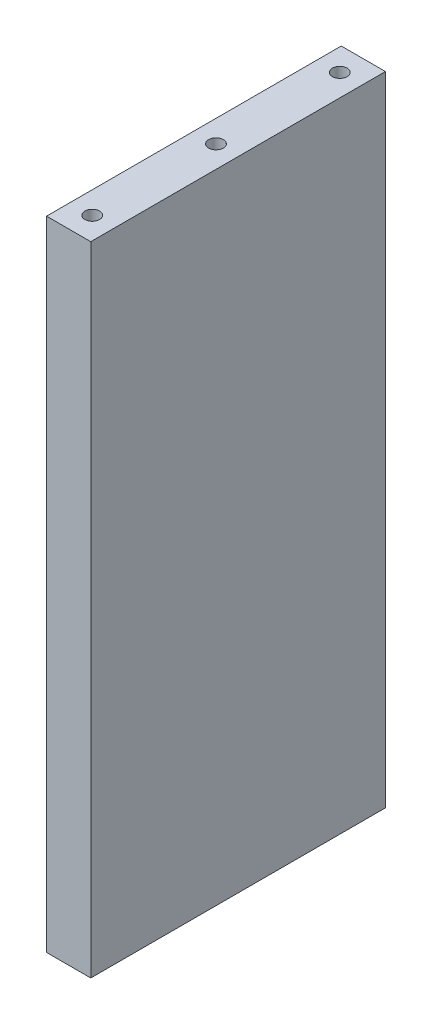
SolidWorks part; units mm, degrees
ref_plane "Front Plane" through (0, 0, 0) normal (0, 0, 1) x (1, 0, 0)
ref_plane "Top Plane" through (0, 0, 0) normal (0, 1, 0) x (1, 0, 0)
ref_plane "Right Plane" through (0, 0, 0) normal (1, 0, 0) x (0, 0, -1)
sketch "Sketch1" plane through (0, 0, 0) normal (0, 0, 1) x (1, 0, 0)
  line L1 (-4.7625, 68.707) -> (4.7625, 68.707)
  line L2 (-4.7625, 68.707) -> (-4.7625, -68.707)
  line L3 (-4.7625, -68.707) -> (4.7625, -68.707)
  line L4 (4.7625, 68.707) -> (4.7625, -68.707)
  point P4 (0, 68.707)
  point P6 (-4.7625, 0)
  dimension "D1" = 137.414
  dimension "D2" = 9.525
extrude "Boss-Extrude1" add sketch "Sketch1" along normal blind 63.5
sketch "Sketch2" plane through (0, 68.707, 0) normal (0, 1, 0) x (1, 0, 0)
  line L0 (4.7625, -63.5) -> (4.7625, 0) construction
  line L1 (-4.7625, -63.5) -> (-4.7625, 0) construction
  circle A0 centre (0, -5.08) radius 1.5875
  circle A1 centre (0, -31.75) radius 1.5875
  circle A2 centre (0, -58.42) radius 1.5875
  point P8 (4.7625, -31.75)
  dimension "D1" = 3.175
  dimension "D2" = 53.34
  dimension "D3" = 26.67
  dimension "D4" = 4.7625
extrude "Cut-Extrude1" cut sketch "Sketch2" against normal blind 9.525
mirror "Mirror1" about plane through (0, 0, 0) normal (0, 1, 0) of "Cut-Extrude1"
